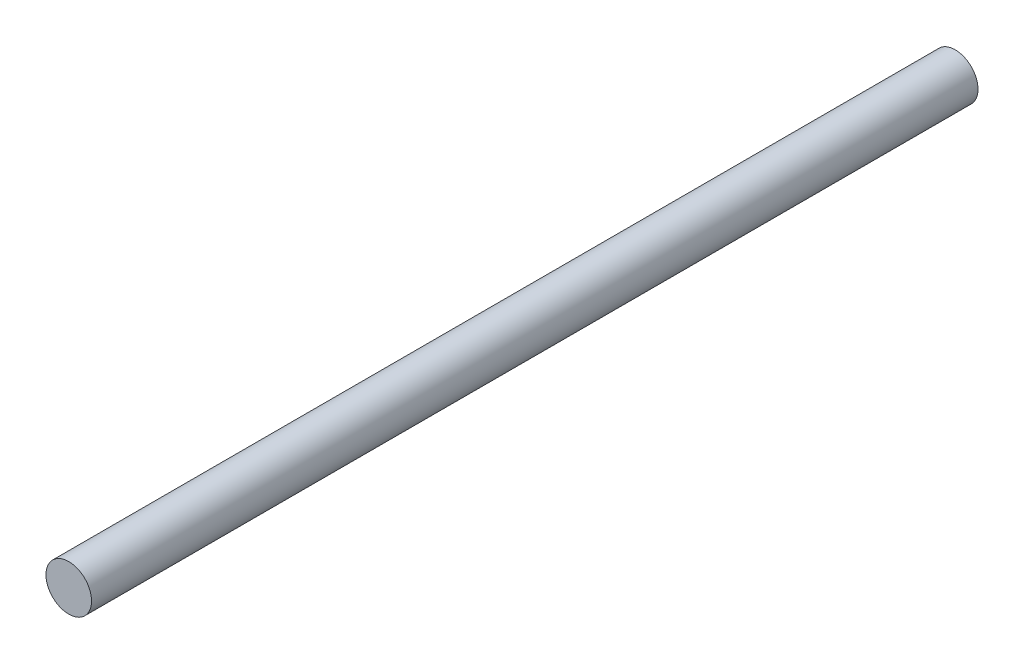
SolidWorks part; units mm, degrees
material "AISI 1020"
ref_plane "Front Plane" through (0, 0, 0) normal (0, 0, 1) x (1, 0, 0)
ref_plane "Top Plane" through (0, 0, 0) normal (0, 1, 0) x (1, 0, 0)
ref_plane "Right Plane" through (0, 0, 0) normal (1, 0, 0) x (0, 0, -1)
other "Configuration Table"
sketch "Sketch1" plane through (0, 0, 0) normal (0, 0, 1) x (1, 0, 0)
  circle A0 centre (0, 0) radius 2.286
  dimension "D1" = 4.572
extrude "Boss-Extrude1" add sketch "Sketch1" along normal mid plane 88.9
scale "Scale1" scale about centroid uniform scaling yes scale factor 1.5
